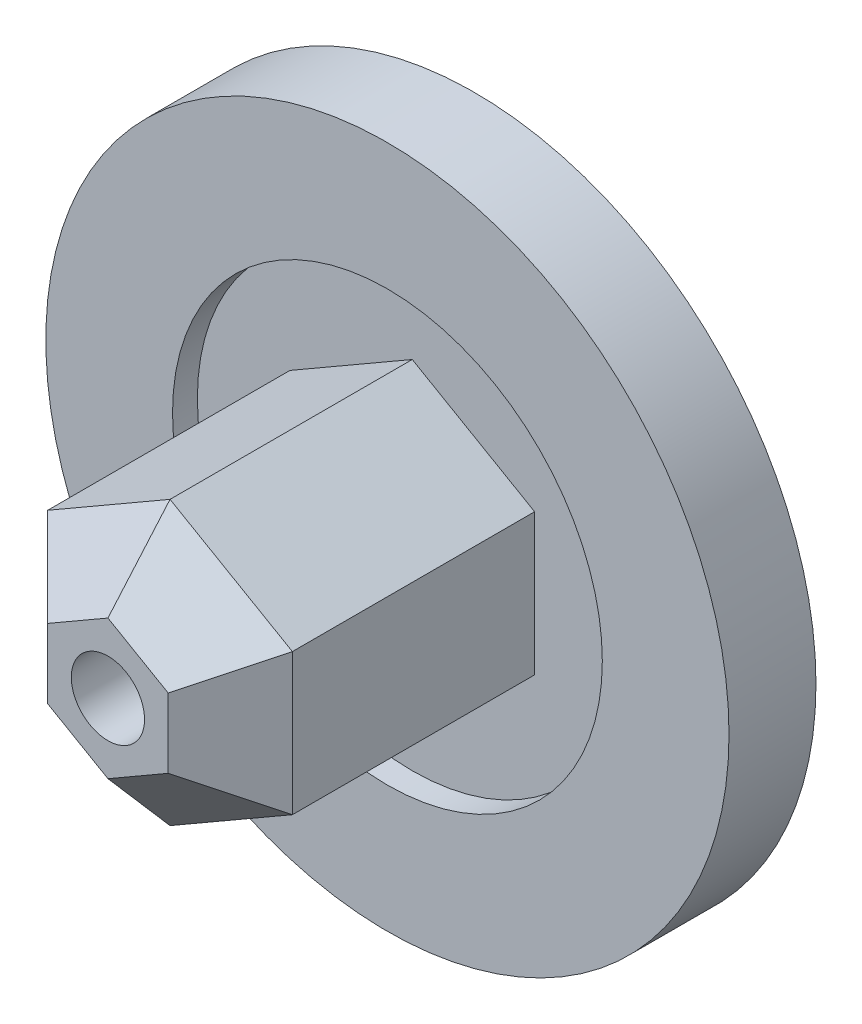
SolidWorks part; units mm, degrees
ref_plane "Front Plane" through (0, 0, 0) normal (0, 0, 1) x (1, 0, 0)
ref_plane "Top Plane" through (0, 0, 0) normal (0, 1, 0) x (1, 0, 0)
ref_plane "Right Plane" through (0, 0, 0) normal (1, 0, 0) x (0, 0, -1)
sketch "Sketch1" plane through (0, 0, 0) normal (0, 0, 1) x (1, 0, 0)
  line L0 (0, 60.8729) -> (0, -58.0763) construction
  line L1 (-81.2881, 0) -> (64.5085, 0) construction
  circle A0 centre (0, 0) radius 27.5
  dimension "D1" = 55
extrude "Boss-Extrude1" add sketch "Sketch1" along normal blind 7
sketch "Sketch2" plane through (0, 0, 7) normal (0, 0, 1) x (1, 0, 0)
  circle A0 centre (0, 0) radius 17.3
  dimension "D1" = 34.6
extrude "Cut-Extrude1" cut sketch "Sketch2" against normal blind 2
sketch "Sketch3" plane through (0, 0, 5) normal (0, 0, 1) x (1, 0, 0)
  line L0 (0, 29.5371) -> (0, -32.0259) construction
  line L2 (0, 11.3738) -> (-9.85, 5.6869)
  line L3 (-9.85, 5.6869) -> (-9.85, -5.6869)
  line L4 (-9.85, -5.6869) -> (0, -11.3738)
  line L5 (0, -11.3738) -> (9.85, -5.6869)
  line L6 (9.85, -5.6869) -> (9.85, 5.6869)
  line L7 (9.85, 5.6869) -> (0, 11.3738)
  circle A0 centre (0, 0) radius 9.85 construction
  dimension "D1" = 19.7
extrude "Boss-Extrude2" add sketch "Sketch3" along normal blind 19.5
sketch "Sketch4" plane through (0, 0, 24.5) normal (0, 0, 1) x (1, 0, 0)
  line L6 (9.85, 5.6869) -> (0, 11.3738)
  line L7 (0, 11.3738) -> (-9.85, 5.6869)
  line L8 (-9.85, 5.6869) -> (-9.85, -5.6869)
  line L9 (-9.85, -5.6869) -> (0, -11.3738)
  line L10 (0, -11.3738) -> (9.85, -5.6869)
  line L11 (9.85, -5.6869) -> (9.85, 5.6869)
  line L12 (9.85, 5.6869) -> (0, 11.3738)
  line L13 (0, 11.3738) -> (-9.85, 5.6869)
  line L14 (-9.85, 5.6869) -> (-9.85, -5.6869)
  line L15 (-9.85, -5.6869) -> (0, -11.3738)
  line L16 (0, -11.3738) -> (9.85, -5.6869)
  line L17 (9.85, -5.6869) -> (9.85, 5.6869)
  dimension "D1" = 0
extrude "Boss-Extrude3" add sketch "Sketch4" along normal blind 5 draft 45
sketch "Sketch5" plane through (0, 0, 0) normal (0, 0, -1) x (-1, 0, 0)
  circle A0 centre (0, 0) radius 7.05
  dimension "D1" = 14.1
extrude "Cut-Extrude2" cut sketch "Sketch5" against normal blind 16.5
sketch "Sketch6" plane through (0, 0, 16.5) normal (0, 0, -1) x (-1, 0, 0)
  circle A0 centre (0, 0) radius 2.95
  dimension "D1" = 5.9
extrude "Cut-Extrude3" cut sketch "Sketch6" against normal through all
sketch "Sketch7" plane through (0, 0, 0) normal (0, 0, -1) x (-1, 0, 0)
  circle A0 centre (0, 0) radius 25.55
  circle A1 centre (0, 0) radius 23.75
  dimension "D1" = 51.1
  dimension "D2" = 47.5
extrude "Cut-Extrude4" cut sketch "Sketch7" against normal blind 5
chamfer "Chamfer1" distance 0.5 2 edges at (-25.55, 0, 0) (-23.75, 0, 0)
